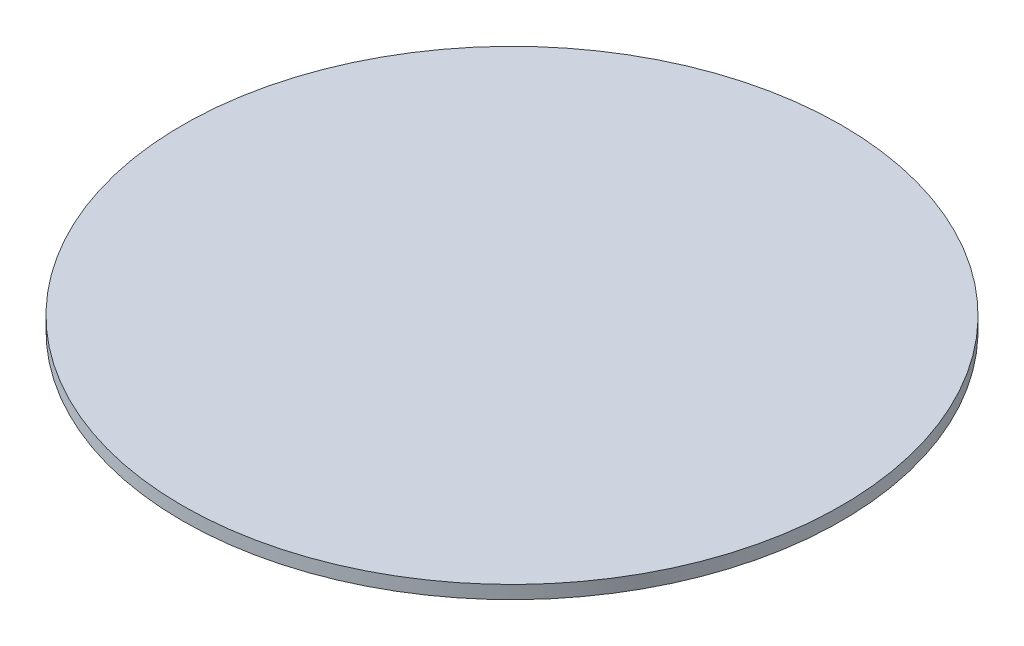
SolidWorks part; units mm, degrees
ref_plane "Front Plane" through (0, 0, 0) normal (0, 0, 1) x (1, 0, 0)
ref_plane "Top Plane" through (0, 0, 0) normal (0, 1, 0) x (1, 0, 0)
ref_plane "Right Plane" through (0, 0, 0) normal (1, 0, 0) x (0, 0, -1)
sketch "Sketch1" plane through (0, 0, 0) normal (0, 1, 0) x (1, 0, 0)
  circle A0 centre (0, 0) radius 25
  dimension "D1" = 50
extrude "Boss-Extrude1" add sketch "Sketch1" along normal blind 1
